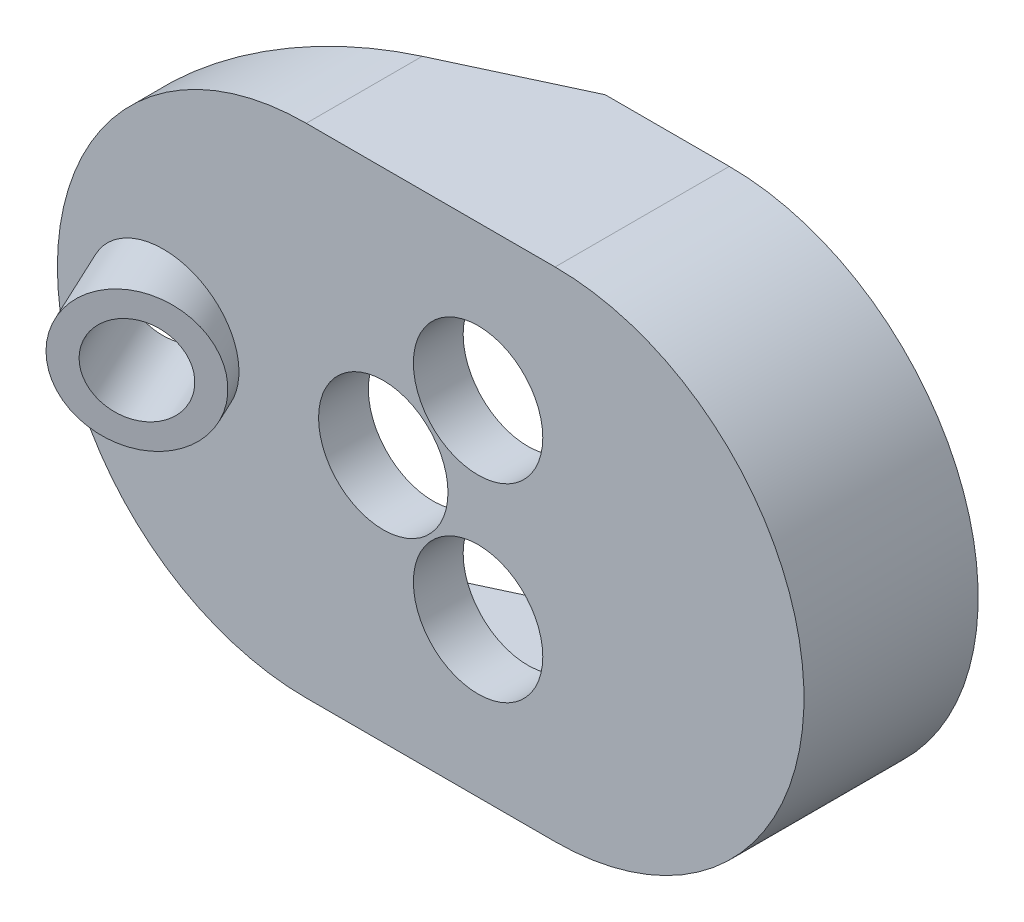
SolidWorks part; units mm, degrees
ref_plane "Front Plane" through (0, 0, 0) normal (0, 0, 1) x (1, 0, 0)
ref_plane "Top Plane" through (0, 0, 0) normal (0, 1, 0) x (1, 0, 0)
ref_plane "Right Plane" through (0, 0, 0) normal (1, 0, 0) x (0, 0, -1)
sketch "Sketch3" plane through (0, 0, 0) normal (0, 0, 1) x (1, 0, 0)
  line L0 (-5, 0) -> (5, 0) construction
  line L1 (-5, 10) -> (5, 10)
  line L2 (-5, -10) -> (5, -10)
  line L3 (1.905, 3.81) -> (1.905, -3.81) construction
  line L4 (-1.905, 0) -> (1.905, -3.81) construction
  line L5 (1.905, 3.81) -> (-1.905, 0) construction
  line L6 (-1.905, 0) -> (1.905, 0) construction
  arc A0 (-5, 10) -> (-5, -10) centre (-5, 0) ccw
  arc A1 (5, -10) -> (5, 10) centre (5, 0) ccw
  circle A2 centre (1.905, 3.81) radius 2.6
  circle A3 centre (1.905, -3.81) radius 2.6
  circle A4 centre (-1.905, 0) radius 2.6
  point P2 (0, 0)
  point P14 (0, 0)
  point P16 (0, 0)
  point P17 (0, 0)
  point P18 (0, 0)
  point P19 (1.905, 0)
  dimension "D2" = 10
  dimension "D3" = 5.2
  dimension "D4" = 5.2
  dimension "D5" = 5.2
  dimension "D1" = 10
  dimension "D6" = 7.62
  dimension "D9" = 45
  dimension "D7" = 90
extrude "Boss-Extrude1" add sketch "Sketch3" along normal blind 7
sketch "Sketch4" plane through (0, 0, 0) normal (0, 0, -1) x (-1, 0, 0)
  line L1 (-8, 8) -> (8, 8)
  line L2 (-8, 8) -> (-8, -8)
  line L3 (-8, -8) -> (8, -8)
  line L4 (8, 8) -> (8, -8)
  line L5 (-8, 8) -> (8, -8) construction
  line L6 (-8, -8) -> (8, 8) construction
  point P0 (0, 0)
  dimension "D1" = 16
  dimension "D2" = 16
extrude "Cut-Extrude1" cut sketch "Sketch4" against normal blind 5
sketch "Sketch5" plane through (0, 0, 0) normal (0, 0, -1) x (-1, 0, 0)
  line L0 (-11.5, -2.5) -> (-11.5, 2.5) construction
  line L1 (1.905, 0) -> (-11.5, 0) construction
  line L2 (-11.5, 0) -> (-15, 0) construction
  circle A0 centre (-11.5, -2.5) radius 2
  circle A1 centre (-11.5, 2.5) radius 2
  arc A2 (-5, 10) -> (-5, -10) centre (-5, 0) ccw construction
  dimension "D1" = 4
  dimension "D2" = 4
  dimension "D3" = 5
  dimension "D4" = 3.5
extrude "Cut-Extrude2" cut sketch "Sketch5" against normal blind 4
sketch "Sketch6" plane through (0, -10, 0) normal (0, -1, 0) x (1, 0, 0)
  line L0 (15, 0) -> (15, 7) construction
  line L1 (-15, 7) -> (-15, 0) construction
  line L2 (-15, 0) -> (-5, 0) construction
  line L3 (-5, 0) -> (5, 0) construction
  line L4 (5, 0) -> (15, 0) construction
  line L5 (15, 7) -> (5, 7) construction
  line L6 (-5, 7) -> (-15, 7) construction
  line L7 (15, 0) -> (15, 7)
  line L8 (-15, 7) -> (-15, 0)
  line L9 (-15, 0) -> (-5, 0)
  line L10 (-5, 0) -> (5, 0)
  line L11 (5, 0) -> (15, 0)
  line L12 (15, 7) -> (5, 7)
  line L13 (-5, 7) -> (-15, 7)
  line L14 (-15, 7) -> (0.0115, 0)
  line M3 (-5, 0) -> (5, 0)
  line M6 (-5, 7) -> (-5, 0)
  dimension "D1" = 25
extrude "Cut-Extrude3" cut sketch "Sketch6" against normal through all contours L14 L8 L9 M6 | L14 M6 M3
sketch "Sketch8" plane through (0.0021, 0, 0.0044) normal (-0.4226, 0, -0.9063) x (-0.9063, 0, 0.4226)
  line L0 (8.8293, 0) -> (12.6911, 0) construction
  line L1 (8.8293, 8) -> (8.8293, -8) construction
  line L2 (12.6911, 0) -> (16.5529, 0) construction
  circle A0 centre (12.6911, 0) radius 1.75
  circle A1 centre (-19.0652, 0) radius 1.75 construction
  dimension "D1" = 3.5
  dimension "D2" = 3.5
extrude "Cut-Extrude4" cut sketch "Sketch8" against normal through all
sketch "Sketch9" plane through (0.0021, 0, 0.0044) normal (-0.4226, 0, -0.9063) x (-0.9063, 0, 0.4226)
  circle A0 centre (12.6911, 0) radius 2.75
  circle A1 centre (12.6911, 0) radius 1.75 construction
  circle A2 centre (12.6911, 0) radius 1.75
  dimension "D1" = 5.5
extrude "Boss-Extrude3" add sketch "Sketch9" against normal blind 4
equation "\"D5@Sketch3\"=\"D4@Sketch3\""
